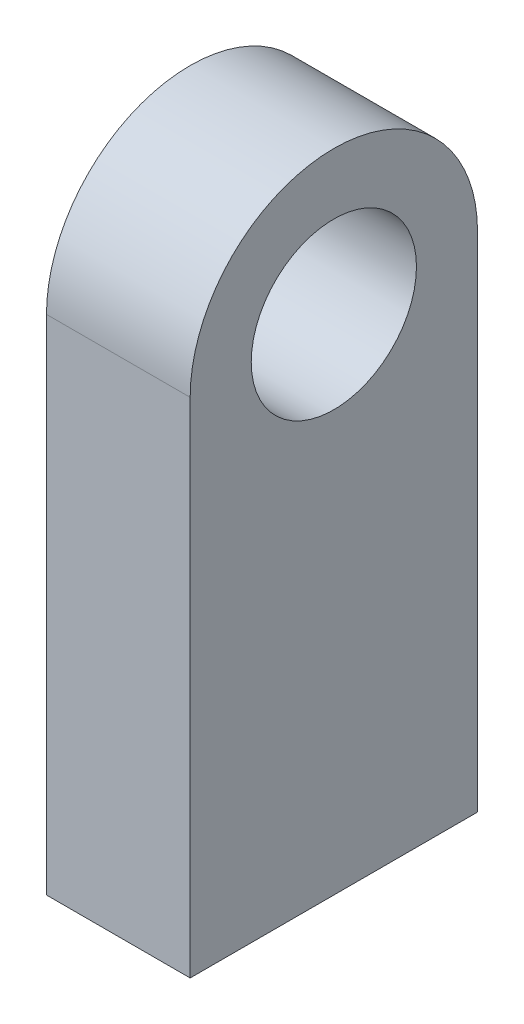
SolidWorks part; units mm, degrees
ref_plane "Front Plane" through (0, 0, 0) normal (0, 0, 1) x (1, 0, 0)
ref_plane "Top Plane" through (0, 0, 0) normal (0, 1, 0) x (1, 0, 0)
ref_plane "Right Plane" through (0, 0, 0) normal (1, 0, 0) x (0, 0, -1)
sketch "Sketch1" plane through (0, 0, 0) normal (1, 0, 0) x (0, 0, -1)
  line L2 (-20, 35) -> (-20, -35)
  line L3 (-20, -35) -> (20, -35)
  line L4 (20, 35) -> (20, -35)
  line L5 (-20, 35) -> (20, -35) construction
  line L6 (-20, -35) -> (20, 35) construction
  arc A0 (-20, 35) -> (20, 35) centre (0, 35) cw
  circle A1 centre (0, 35) radius 11.5
  point P0 (0, 0)
  dimension "D3" = 23
  dimension "D1" = 70
  dimension "D2" = 40
extrude "Boss-Extrude1" add sketch "Sketch1" along normal blind 20
